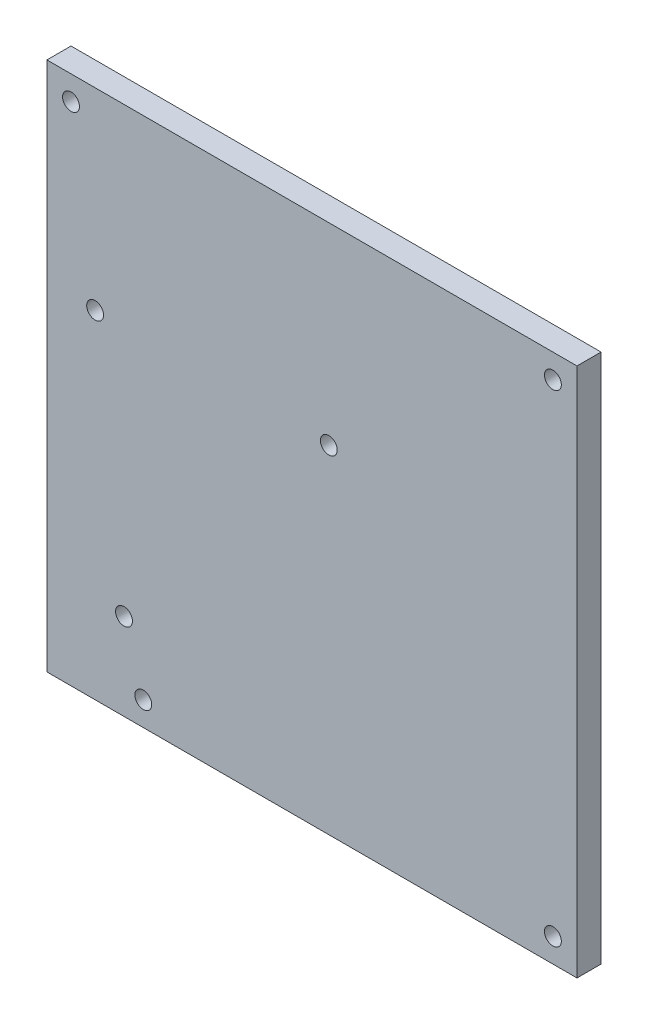
SolidWorks part; units mm, degrees
ref_plane "前视基准面" through (0, 0, 0) normal (0, 0, 1) x (1, 0, 0)
ref_plane "上视基准面" through (0, 0, 0) normal (0, 1, 0) x (1, 0, 0)
ref_plane "右视基准面" through (0, 0, 0) normal (1, 0, 0) x (0, 0, -1)
sketch "草图1" plane through (0, 0, 0) normal (0, 0, 1) x (1, 0, 0)
  line L1 (0, 0) -> (110, 0)
  line L2 (0, 0) -> (0, -110)
  line L3 (0, -110) -> (110, -110)
  line L4 (110, 0) -> (110, -110)
  circle A0 centre (5, -5) radius 1.75
  circle A1 centre (105, -5) radius 1.75
  circle A2 centre (20, -105) radius 1.75
  circle A3 centre (105, -105) radius 1.75
  circle A4 centre (10, -40) radius 1.75
  circle A5 centre (58.5, -40) radius 1.75
  circle A6 centre (16, -92) radius 1.75
  dimension "D3" = 5
  dimension "D4" = 5
  dimension "D5" = 5
  dimension "D6" = 5
  dimension "D7" = 5
  dimension "D8" = 5
  dimension "D9" = 5
  dimension "D10" = 20
  dimension "D11" = 3.5
  dimension "D12" = 3.5
  dimension "D13" = 3.5
  dimension "D14" = 3.5
  dimension "D15" = 3.5
  dimension "D16" = 3.5
  dimension "D17" = 3.5
  dimension "D18" = 48.5
  dimension "D19" = 52
  dimension "D20" = 6
  dimension "D21" = 10
  dimension "D22" = 40
  dimension "D23" = 40
  dimension "D1" = 110
  dimension "D2" = 110
extrude "凸台-拉伸1" add sketch "草图1" along normal blind 5
